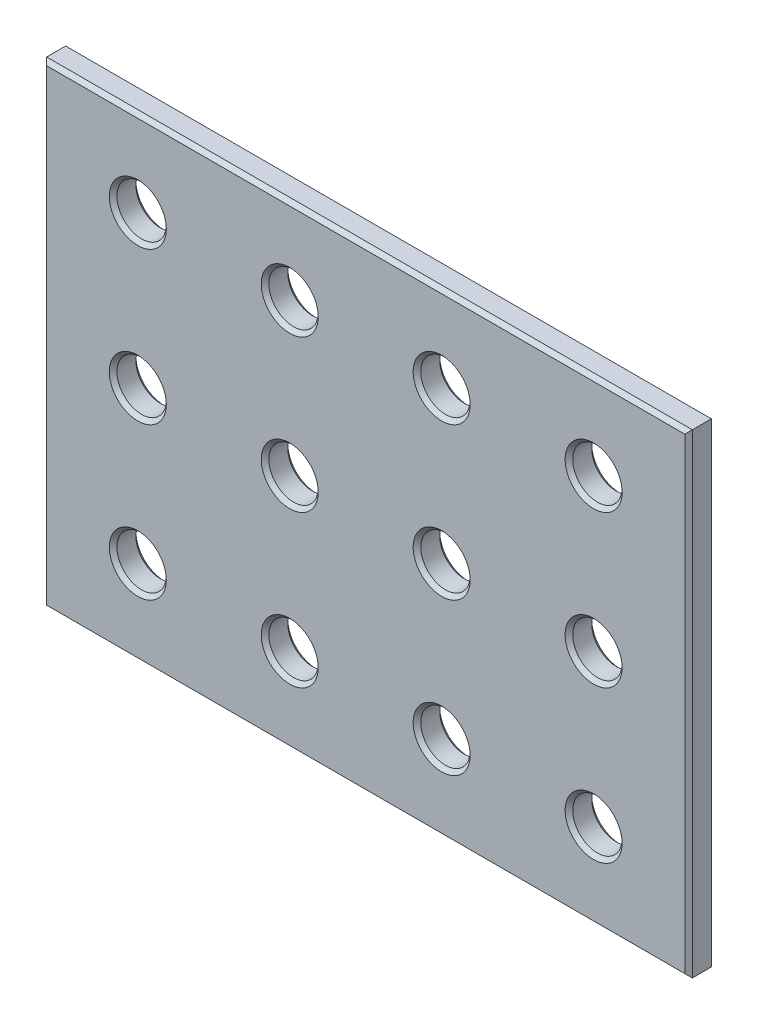
SolidWorks part; units mm, degrees
ref_plane "前视" through (0, 0, 0) normal (0, 0, 1) x (1, 0, 0)
ref_plane "上视" through (0, 0, 0) normal (0, 1, 0) x (1, 0, 0)
ref_plane "右视" through (0, 0, 0) normal (1, 0, 0) x (0, 0, -1)
sketch "草图1" plane through (0, 0, 0) normal (0, 0, 1) x (1, 0, 0)
  line L0 (-97.449, 0) -> (100.3893, 0) construction
  line L1 (-170, 125) -> (170, 125)
  line L2 (-170, 125) -> (-170, -125)
  line L3 (-170, -125) -> (170, -125)
  line L4 (170, 125) -> (170, -125)
  line L5 (-120, 169.1177) -> (-120, -68.0463) construction
  line L7 (-102.0695, 80) -> (112.1504, 80) construction
  line L8 (0, -72.6667) -> (0, 86.108) construction
  circle A0 centre (-120, 80) radius 13
  circle A1 centre (-40, 80) radius 13
  circle A2 centre (-40, 0) radius 13
  circle A3 centre (-120, 0) radius 13
  circle A4 centre (-40, -80) radius 13
  circle A5 centre (-120, -80) radius 13
  circle A6 centre (120, -80) radius 13
  circle A7 centre (40, -80) radius 13
  circle A8 centre (120, 0) radius 13
  circle A9 centre (40, 0) radius 13
  circle A10 centre (40, 80) radius 13
  circle A11 centre (120, 80) radius 13
  dimension "D1" = 250
  dimension "D2" = 340
  dimension "D3" = 80
  dimension "D4" = 50
extrude "基体-拉伸" add sketch "草图1" along normal blind 14
chamfer "倒角1" distance 2 angle 45 32 edges at (107, 80, 0) (27, 0, 0) (53, -80, 0) (-133, -80, 0) (-107, 0, 0) (-27, 80, 0) (0, -125, 0) (170, 0, 0) (0, 125, 0) (-170, 0, 0) (-107, 80, 0) (-27, 0, 0) (-53, -80, 0) (133, -80, 0) (107, 0, 0) (27, 80, 0) (107, 80, 14) (27, 0, 14) (53, -80, 14) (-133, -80, 14) (-107, 0, 14) (-27, 80, 14) (0, 125, 14) (170, 0, 14) (0, -125, 14) (-170, 0, 14) (-107, 80, 14) (-27, 0, 14) (-53, -80, 14) (133, -80, 14) (107, 0, 14) (27, 80, 14)
